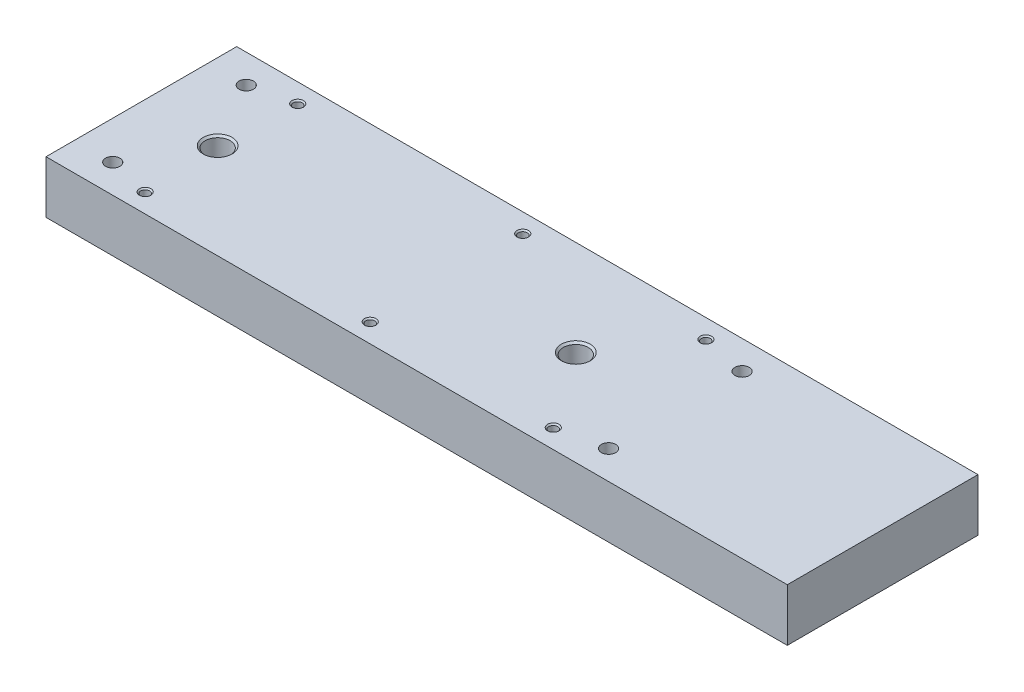
SolidWorks part; units mm, degrees
material "PC High Viscosity"
ref_plane "Front Plane" through (0, 0, 0) normal (0, 0, 1) x (1, 0, 0)
ref_plane "Top Plane" through (0, 0, 0) normal (0, 1, 0) x (1, 0, 0)
ref_plane "Right Plane" through (0, 0, 0) normal (1, 0, 0) x (0, 0, -1)
sketch "Sketch1" plane through (0, 0, 0) normal (0, 1, 0) x (1, 0, 0)
  line L1 (-95.25, -31.75) -> (151.575, -31.75)
  line L2 (-95.25, -31.75) -> (-95.25, 31.75)
  line L3 (-95.25, 31.75) -> (151.575, 31.75)
  line L4 (151.575, -31.75) -> (151.575, 31.75)
  point P0 (0, 0)
  point P7 (82.55, -22.225)
  point P8 (44.45, -22.225)
  point P10 (82.55, 22.225)
  point P11 (44.45, 22.225)
  point P12 (19.05, -22.225)
  point P13 (19.05, 22.225)
  point P16 (-6.35, -22.225)
  point P17 (-6.35, 22.225)
  point P18 (-31.75, -22.225)
  point P19 (-31.75, 22.225)
  point P20 (-57.15, -22.225)
  point P21 (-57.15, 22.225)
  point P22 (-82.55, -22.225)
  point P23 (-82.55, 22.225)
  dimension "D1" = 63.5
  dimension "D3" = 44.45
  dimension "D6" = 6
extrude "Boss-Extrude1" add sketch "Sketch1" along normal blind 17.5
hole_wizard "Hole1" positions "Sketch3" profile "Sketch2" legacy end condition through all
sketch "Sketch3" plane through (0, 0, 0) normal (0, -1, 0) x (1, 0, 0)
  point P0 (82.55, 22.225)
  point P1 (82.55, -22.225)
  point P14 (-82.55, 22.225)
  point P41 (-82.55, -22.225)
sketch "Sketch2" plane through (82.55, 0, 22.225) normal (1, 0, 0) x (0, 0, -1)
  line L0 (0, 0) -> (0, 17.5)
  line L1 (0, 17.5) -> (2.3812, 17.5)
  line L3 (2.3812, 5.029) -> (2.75, 4.6602)
  line L4 (2.75, 4.6602) -> (4.1275, 4.6602)
  line L5 (4.1275, 4.6602) -> (4.1275, 0.6225)
  line L6 (4.1275, 0.6225) -> (4.75, 0)
  line L7 (4.75, 0) -> (0, 0)
  line L8 (-4.1275, 0.6225) -> (-4.75, 0) construction
  line L9 (-2.3813, 5.0289) -> (-2.75, 4.6602) construction
  line L10 (2.3812, 17.5) -> (2.3812, 5.029)
  line L11 (0, -6.35) -> (0, 107.95) construction
  dimension "Thru Hole Dia." = 4.7625
  dimension "Thru Hole Depth" = 17.5
  dimension "C'Bore Dia." = 8.255
  dimension "C'Bore Depth" = 4.6602
  dimension "Near C'Sink Dia." = 9.5
  dimension "Near C'Sink Angle" = 90
  dimension "Mid C'Sink Dia." = 5.5
  dimension "Mid C'Sink Angle" = 90
hole_wizard "#4 Clearance Hole1" positions "Sketch5" profile "Sketch4" counterbore size "#4" standard "Ansi Inch" end condition through all
sketch "Sketch5" plane through (0, 0, 0) normal (0, -1, 0) x (1, 0, 0)
  line L1 (151.575, -31.75) -> (-95.25, -31.75) construction
  line L2 (134.6933, 0) -> (383.0945, 0) construction
  line L3 (0, 0) -> (0, 159.0319) construction
  line L5 (170.452, -25.4) -> (454.0388, -25.4) construction
  point P0 (-68.58, -25.4)
  point P23 (6.35, -25.4)
  point P33 (67.31, -25.4)
  point P36 (-68.58, 25.4)
  point P37 (6.35, 25.4)
  point P38 (67.31, 25.4)
  dimension "D1" = 6.35
  dimension "D2" = 68.58
  dimension "D3" = 6.35
  dimension "D4" = 67.31
sketch "Sketch4" plane through (-68.58, 0, -25.4) normal (1, 0, 0) x (0, 0, -1)
  line L0 (0, 0) -> (0, 17.5)
  line L1 (1.4732, 17.0682) -> (1.905, 17.5)
  line L2 (1.4732, 17.0682) -> (1.4732, 2.9718)
  line L3 (1.4732, 2.9718) -> (1.905, 2.54)
  line L4 (1.905, 2.54) -> (3.175, 2.54)
  line L5 (3.175, 2.54) -> (3.175, 0.254)
  line L6 (3.175, 0.254) -> (3.429, 0)
  line L7 (3.429, 0) -> (0, 0)
  line L8 (-3.175, 0.254) -> (-3.429, 0) construction
  line L9 (-1.4732, 2.9718) -> (-1.905, 2.54) construction
  line L11 (0, -6.35) -> (0, 107.95) construction
  line L12 (1.905, 17.5) -> (0, 17.5)
  line L13 (-1.4732, 17.0682) -> (-1.905, 17.5) construction
  dimension "Thru Hole Dia." = 2.9464
  dimension "Thru Hole Depth" = 17.5
  dimension "C'Bore Dia." = 6.35
  dimension "C'Bore Depth" = 2.54
  dimension "Near C'Sink Dia." = 6.858
  dimension "Near C'Sink Angle" = 90
  dimension "Mid C'Sink Dia." = 3.81
  dimension "Mid C'Sink Angle" = 90
  dimension "Far C'Sink Dia." = 3.81
  dimension "Far C'Sink Angle" = 90
hole_wizard "21/64 (0.32813) Diameter Hole1" positions "Sketch9" profile "Sketch8" hole size "21/64" standard "Ansi Inch" end condition up to next
sketch "Sketch9" plane through (0, 0, 0) normal (0, -1, 0) x (1, 0, 0)
  line L0 (-71.3184, 0) -> (163.6069, 0) construction
  line L1 (55, 0) -> (-55, 0) construction
  line L2 (0, 24.9694) -> (0, -123.0443) construction
  line L3 (0, -55) -> (0, 55) construction
  line L4 (-95.25, -31.75) -> (-95.25, 31.75) construction
  point P26 (-69.85, 0)
  point P28 (49.403, 0)
  dimension "D3" = 119.253
  dimension "D4" = 25.4
sketch "Sketch8" plane through (-69.85, 0, 0) normal (1, 0, 0) x (0, 0, -1)
  line L0 (0, 0) -> (0, 17.5)
  line L1 (0, 17.5) -> (4.8023, 17.5)
  line L2 (4.1673, 16.865) -> (4.1673, 0.635)
  line L3 (4.1673, 0.635) -> (4.8023, 0)
  line L5 (4.8023, 0) -> (0, 0)
  line L6 (-4.1673, 0.635) -> (-4.8023, 0) construction
  line L7 (4.8023, 17.5) -> (4.1673, 16.865)
  line L8 (-4.8023, 17.5) -> (-4.1673, 16.865) construction
  line L11 (0, -6.35) -> (0, 107.95) construction
  dimension "Thru Hole Dia." = 8.3345
  dimension "Thru Hole Depth" = 17.5
  dimension "Near C'Sink Dia." = 9.6045
  dimension "Near C'Sink Angle" = 90
  dimension "Far C'Sink Dia." = 9.6045
  dimension "Far C'Sink Angle" = 90
